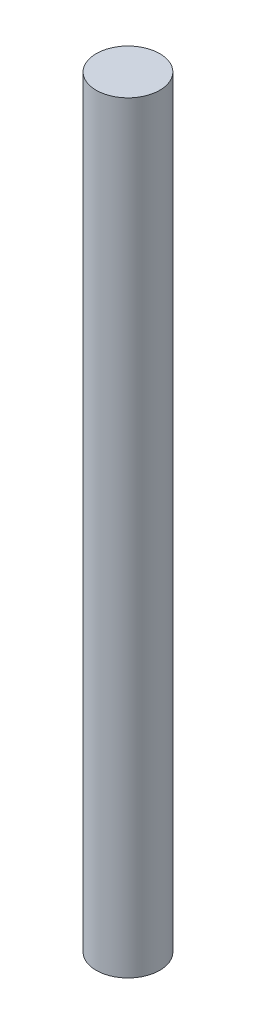
SolidWorks part; units mm, degrees
ref_plane "Front Plane" through (0, 0, 0) normal (0, 0, 1) x (1, 0, 0)
ref_plane "Top Plane" through (0, 0, 0) normal (0, 1, 0) x (1, 0, 0)
ref_plane "Right Plane" through (0, 0, 0) normal (1, 0, 0) x (0, 0, -1)
sketch "Sketch1" plane through (0, 0, 0) normal (0, 1, 0) x (1, 0, 0)
  circle A0 centre (0, 0) radius 0.5
  dimension "D1" = 1
extrude "Boss-Extrude1" add sketch "Sketch1" along normal blind 12
